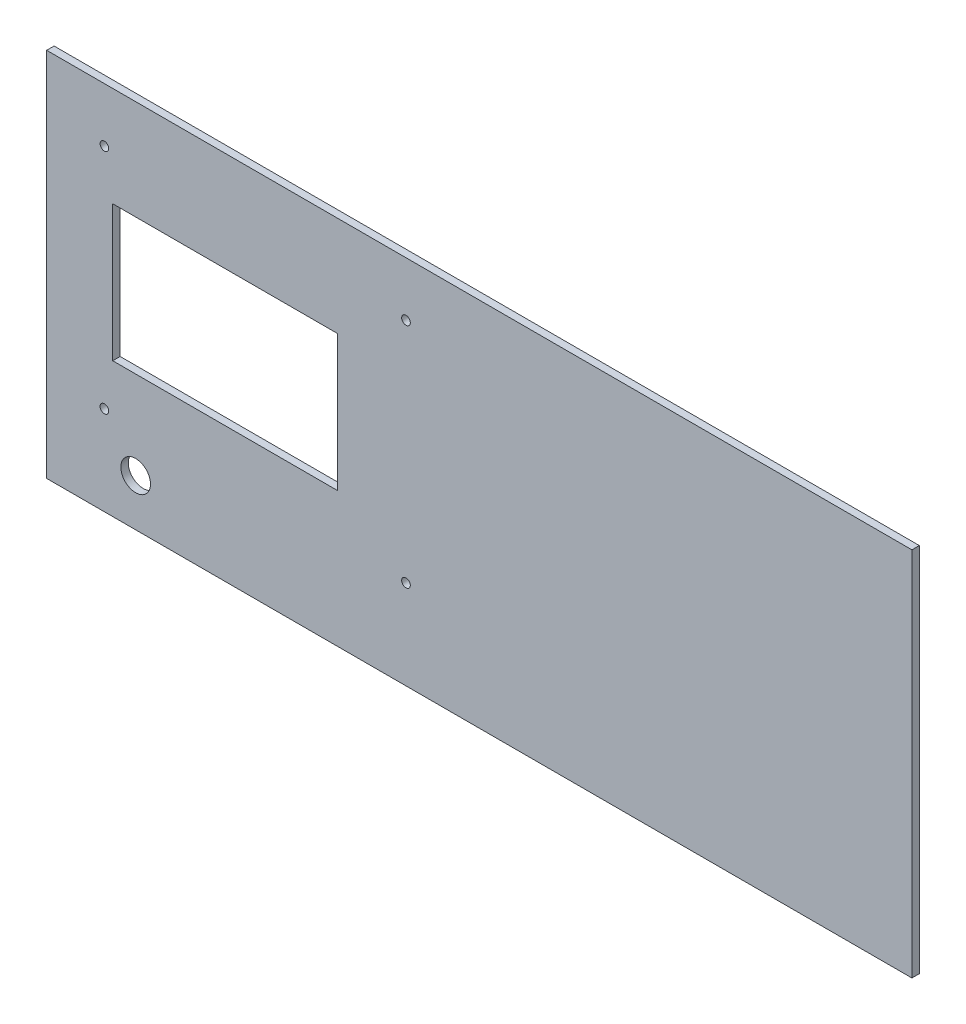
SolidWorks part; units mm, degrees
ref_plane "前视基准面" through (0, 0, 0) normal (0, 0, 1) x (1, 0, 0)
ref_plane "上视基准面" through (0, 0, 0) normal (0, 1, 0) x (1, 0, 0)
ref_plane "右视基准面" through (0, 0, 0) normal (1, 0, 0) x (0, 0, -1)
sketch "草图1" plane through (0, 0, 0) normal (0, 0, 1) x (1, 0, 0)
  line L0 (-57.2774, 110.5955) -> (-57.2774, 53.5955) construction
  line L1 (-52.2774, 109.5955) -> (-148.2774, 109.5955) construction
  line L3 (-148.2774, 109.5955) -> (-148.2774, 54.5955) construction
  line L4 (-149.2774, 110.5955) -> (-149.2774, 53.5955)
  line L5 (-149.2774, 53.5955) -> (-52.2774, 53.5955)
  line L6 (-52.2774, 53.5955) -> (-52.2774, 110.5955)
  line L7 (-52.2774, 110.5955) -> (-149.2774, 110.5955)
  line L8 (-149.2774, 110.5955) -> (-149.2774, 53.5955) construction
  line L9 (-149.2774, 53.5955) -> (-52.2774, 53.5955) construction
  line L10 (-52.2774, 53.5955) -> (-52.2774, 110.5955) construction
  line L11 (-52.2774, 110.5955) -> (-149.2774, 110.5955) construction
  line L19 (-175, 150) -> (-175, 0)
  line L20 (-175, 0) -> (175, 0)
  line L21 (175, 0) -> (175, 150)
  line L22 (175, 150) -> (-175, 150)
  line L23 (-175, 150) -> (-175, 0)
  line L24 (-175, 0) -> (175, 0)
  line L25 (175, 0) -> (175, 150)
  line L26 (175, 150) -> (-175, 150)
  line L383 (-148.2774, 54.5955) -> (-52.2774, 54.5955) construction
  line L385 (-57.2774, 109.5955) -> (-148.2774, 109.5955)
  line L386 (-57.2774, 109.5955) -> (-57.2774, 54.5955)
  line L387 (-57.2774, 54.5955) -> (-148.2774, 54.5955)
  line L388 (-148.2774, 109.5955) -> (-148.2774, 54.5955)
  circle A0 centre (-29.6524, 36.0955) radius 3 construction
  circle A1 centre (-151.6524, 36.0955) radius 3
  circle A2 centre (-151.6524, 36.0955) radius 3 construction
  circle A3 centre (-151.6524, 128.0955) radius 3
  circle A4 centre (-151.6524, 128.0955) radius 3 construction
  circle A5 centre (-29.6524, 128.0955) radius 3 construction
  circle A6 centre (-29.6524, 36.0955) radius 3 construction
  circle A7 centre (-29.6524, 128.0955) radius 3 construction
  circle A8 centre (-151.6524, 128.0955) radius 1.75
  circle A9 centre (-29.6524, 128.0955) radius 1.75
  circle A10 centre (-29.6524, 36.0955) radius 1.75
  circle A11 centre (-151.6524, 36.0955) radius 1.75
  circle A12 centre (-139, 19) radius 6
  circle A39 centre (-139, 19) radius 8.5 construction
  dimension "D6" = 3.5
  dimension "D7" = 3.5
  dimension "D8" = 3.5
  dimension "D9" = 3.5
  dimension "D13" = 12
  dimension "D14" = 17
  dimension "D11" = 19
  dimension "D12" = 36
  dimension "D2" = 5
  dimension "D1" = 0
  dimension "D4" = 0
  dimension "D5" = 0
  dimension "D10" = 0
  dimension "D3" = 1
extrude "凸台-拉伸1" add sketch "草图1" along normal blind 3
equation "\"D7@草图1\"=\"D6@草图1\""
equation "\"D8@草图1\"=\"D6@草图1\""
equation "\"D9@草图1\"=\"D6@草图1\""
